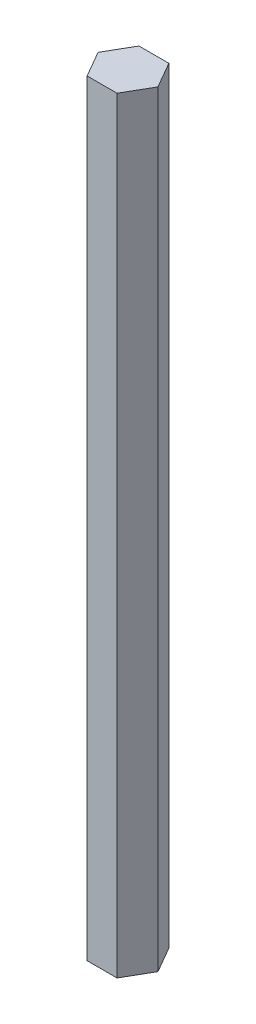
SolidWorks part; units mm, degrees
ref_plane "Front Plane" through (0, 0, 0) normal (0, 0, 1) x (1, 0, 0)
ref_plane "Top Plane" through (0, 0, 0) normal (0, 1, 0) x (1, 0, 0)
ref_plane "Right Plane" through (0, 0, 0) normal (1, 0, 0) x (0, 0, -1)
sketch "Sketch1" plane through (0, 0, 0) normal (0, 1, 0) x (1, 0, 0)
  line L1 (7.9771, 1.5793) -> (3.9771, 8.5075)
  line L2 (3.9771, 8.5075) -> (-4.0229, 8.5075)
  line L3 (-4.0229, 8.5075) -> (-8.0229, 1.5793)
  line L4 (-8.0229, 1.5793) -> (-4.0229, -5.3489)
  line L5 (-4.0229, -5.3489) -> (3.9771, -5.3489)
  line L6 (3.9771, -5.3489) -> (7.9771, 1.5793)
  circle A0 centre (-0.0229, 1.5793) radius 6.9282 construction
  dimension "D1" = 8
extrude "Boss-Extrude1" add sketch "Sketch1" along normal blind 204.79
